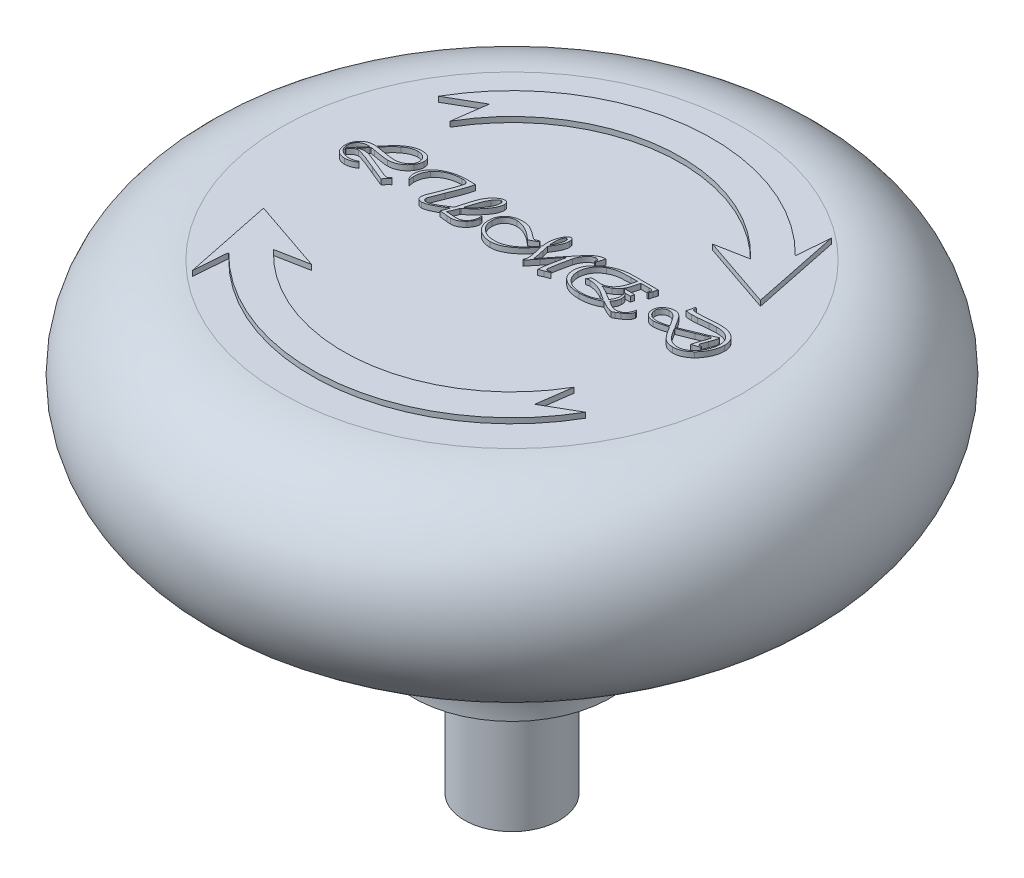
SolidWorks part; units mm, degrees
ref_plane "Front" through (0, 0, 0) normal (0, 0, 1) x (1, 0, 0)
ref_plane "Top" through (0, 0, 0) normal (0, 1, 0) x (-1, 0, 0)
ref_plane "Right" through (0, 0, 0) normal (1, 0, 0) x (0, 0, -1)
sketch "Sketch1" plane through (0, 0, 0) normal (0, 0, 1) x (1, 0, 0)
  line L0 (0, 0) -> (0, 36.2882) construction
  line L1 (0, 0) -> (0, 22.225)
  line L2 (0, 22.225) -> (11.1125, 22.225)
  line L4 (4.7625, 6.35) -> (2.286, 6.35)
  line L5 (2.286, 6.35) -> (2.286, 0)
  line L6 (2.286, 0) -> (0, 0)
  arc A0 (11.1125, 22.225) -> (11.1125, 12.7) centre (11.1125, 17.4625) cw
  arc A1 (11.1125, 12.7) -> (4.7625, 6.35) centre (11.1125, 6.35) ccw
  dimension "D5" = 6.35
  dimension "D6" = 4.7625
  dimension "D1" = 4.572
  dimension "D2" = 4.7625
  dimension "D3" = 6.35
  dimension "D4" = 15.875
revolve "Base-Revolve" add sketch "Sketch1" angle 360 about L0
ref_plane "Plane1" through (0, 22.225, 0) normal (0, 1, 0) x (1, 0, 0)
sketch "Sketch2" plane through (0, 22.225, 0) normal (0, 1, 0) x (1, 0, 0)
  line L0 (-11.1125, 0) -> (11.1125, 0) construction
  circle A0 centre (0, 0) radius 11.1125 construction
  text T0 "LUMED" font "@Adobe Fan Heiti Std B" height 2.032
extrude "Boss-Extrude1" add sketch "Sketch2" along normal blind 0.254
sketch "Sketch3" plane through (0, 22.225, 0) normal (0, 1, 0) x (1, 0, 0)
  line L0 (-7.0391, 4.064) -> (-6.8101, 5.7144)
  line L1 (-6.8101, 5.7144) -> (-8.3589, 4.826)
  line L2 (7.9067, 4.064) -> (4.4082, 5.2535)
  line L3 (4.4082, 5.2535) -> (5.9405, 5.5475)
  line L4 (6.8928, 6.7565) -> (7.0205, 8.3667)
  line L5 (7.0205, 8.3667) -> (7.9067, 4.064)
  line L6 (0, 0) -> (0, 8.128) construction
  line L7 (-6.8101, 5.7144) -> (0, 0) construction
  line L8 (0, 0) -> (-8.3589, 4.826) construction
  line L9 (0, 0) -> (7.9067, 4.064) construction
  line L10 (0, 0) -> (6.8101, 5.7144) construction
  line L11 (0, 0) -> (5.7144, 6.8101) construction
  circle A0 centre (0, 0) radius 8.89 construction
  arc A1 (6.8928, 6.7565) -> (-8.3589, 4.826) centre (0, 0) ccw
  arc A2 (5.9405, 5.5475) -> (-7.0391, 4.064) centre (0, 0) ccw
  circle A3 centre (0, 0) radius 8.128 construction
  circle A4 centre (0, 0) radius 9.652 construction
  dimension "D1" = 17.78
  dimension "D4" = 10
  dimension "D5" = 50
  dimension "D6" = 10
  dimension "D7" = 1.27
  dimension "D8" = 1.27
  dimension "D2" = 0.762
  dimension "D3" = 0.762
extrude "Boss-Extrude2" add sketch "Sketch3" along normal blind 0.254
pattern_circular "CirPattern1" count 2 over 360 about axis through (0, 0, 0) along (0, 1, 0) of "Boss-Extrude2"
